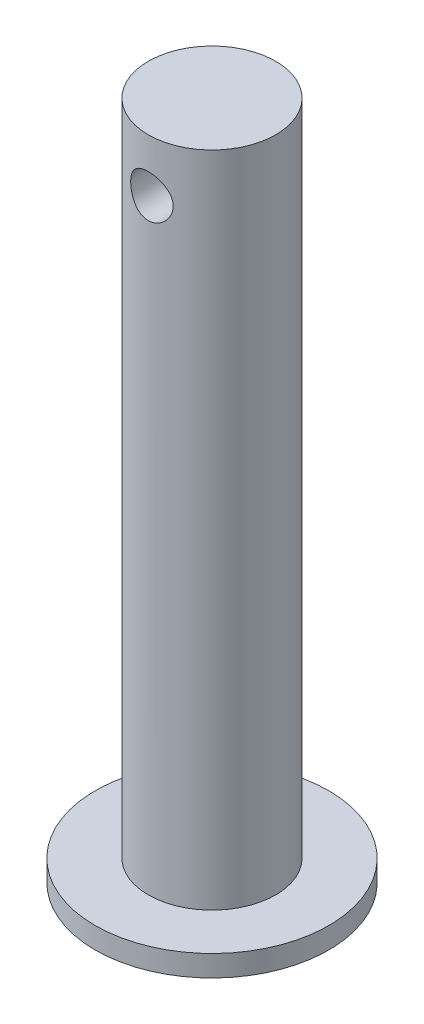
SolidWorks part; units mm, degrees
ref_plane "Front Plane" through (0, 0, 0) normal (0, 0, 1) x (1, 0, 0)
ref_plane "Top Plane" through (0, 0, 0) normal (0, 1, 0) x (1, 0, 0)
ref_plane "Right Plane" through (0, 0, 0) normal (1, 0, 0) x (0, 0, -1)
sketch "Sketch1" plane through (0, 0, 0) normal (0, 1, 0) x (1, 0, 0)
  circle A0 centre (0, 0) radius 5.5
  dimension "D1" = 11
extrude "Boss-Extrude1" add sketch "Sketch1" along normal blind 1
sketch "Sketch2" plane through (0, 1, 0) normal (0, 1, 0) x (1, 0, 0)
  circle A0 centre (0, 0) radius 3
  dimension "D1" = 6
extrude "Boss-Extrude2" add sketch "Sketch2" along normal blind 31
sketch "Sketch3" plane through (0, 0, 0) normal (0, 0, 1) x (1, 0, 0)
  line L0 (0, 32) -> (0, 29.5) construction
  line L1 (3, 32) -> (-3, 32) construction
  circle A0 centre (0, 29.5) radius 1
  dimension "D2" = 2
  dimension "D1" = 2.5
extrude "Cut-Extrude1" cut sketch "Sketch3" against normal mid plane 31
